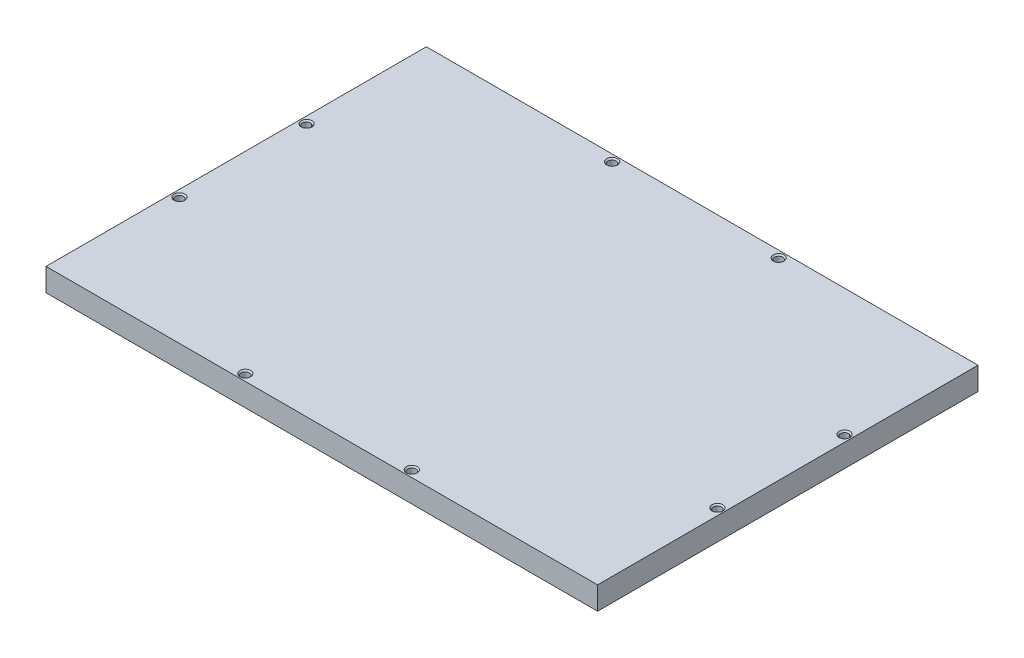
SolidWorks part; units mm, degrees
ref_plane "Front Plane" through (0, 0, 0) normal (0, 0, 1) x (1, 0, 0)
ref_plane "Top Plane" through (0, 0, 0) normal (0, 1, 0) x (1, 0, 0)
ref_plane "Right Plane" through (0, 0, 0) normal (1, 0, 0) x (0, 0, -1)
sketch "Sketch1" plane through (0, 0, 0) normal (0, 1, 0) x (1, 0, 0)
  line L0 (3.175, 0) -> (3.175, -177.8) construction
  line L1 (0, 0) -> (257.81, 0)
  line L2 (0, 0) -> (0, -177.8)
  line L3 (0, -177.8) -> (257.81, -177.8)
  line L4 (257.81, 0) -> (257.81, -177.8)
  line L5 (0, -59.182) -> (257.81, -59.182) construction
  line L6 (0, -118.618) -> (257.81, -118.618) construction
  line L7 (89.9922, 0) -> (89.9922, -177.8) construction
  line L8 (167.8178, 0) -> (167.8178, -177.8) construction
  line L9 (254.635, 0) -> (254.635, -177.8) construction
  line L10 (0, -174.625) -> (257.81, -174.625) construction
  line L11 (0, -3.175) -> (257.81, -3.175) construction
  point P21 (3.175, -118.618)
  point P22 (3.175, -59.182)
  point P23 (167.8178, -3.175)
  point P24 (254.635, -59.182)
  point P25 (89.9922, -3.175)
  point P26 (167.8178, -174.625)
  point P27 (254.635, -118.618)
  point P28 (89.9922, -174.625)
  dimension "D1" = 257.81
  dimension "D2" = 177.8
  dimension "D3" = 3.175
  dimension "D4" = 3.175
  dimension "D5" = 3.175
  dimension "D6" = 3.175
  dimension "D7" = 59.182
  dimension "D8" = 59.182
  dimension "D9" = 89.9922
  dimension "D10" = 89.9922
extrude "Boss-Extrude1" add sketch "Sketch1" along normal blind 10.6874
hole_wizard "#6 Clearance Hole1" positions "Sketch4" profile "Sketch5" hole size "#6" standard "ANSI Inch" end condition through all
sketch "Sketch4" plane through (0, 10.6874, 0) normal (0, 1, 0) x (1, 0, 0)
  point P0 (3.175, -59.182)
  point P3 (89.9922, -3.175)
  point P6 (3.175, -118.618)
  point P10 (167.8178, -3.175)
  point P13 (254.635, -59.182)
  point P16 (254.635, -118.618)
  point P19 (167.8178, -174.625)
  point P22 (89.9922, -174.625)
sketch "Sketch5" plane through (3.175, 10.6874, 59.182) normal (1, 0, 0) x (0, 0, 1)
  line L0 (0, 0) -> (0, 10.6874)
  line L1 (0, 10.6874) -> (1.8986, 10.6874)
  line L2 (1.8986, 10.6874) -> (1.8986, 0.635)
  line L3 (1.8986, 0.635) -> (2.5337, 0)
  line L5 (2.5337, 0) -> (0, 0)
  line L6 (-1.8986, 0.635) -> (-2.5337, 0) construction
  line L11 (0, -6.35) -> (0, 107.95) construction
  dimension "Thru Hole Dia." = 3.7973
  dimension "Thru Hole Depth" = 10.6874
  dimension "Near C'Sink Dia." = 5.0673
  dimension "Near C'Sink Angle" = 90
